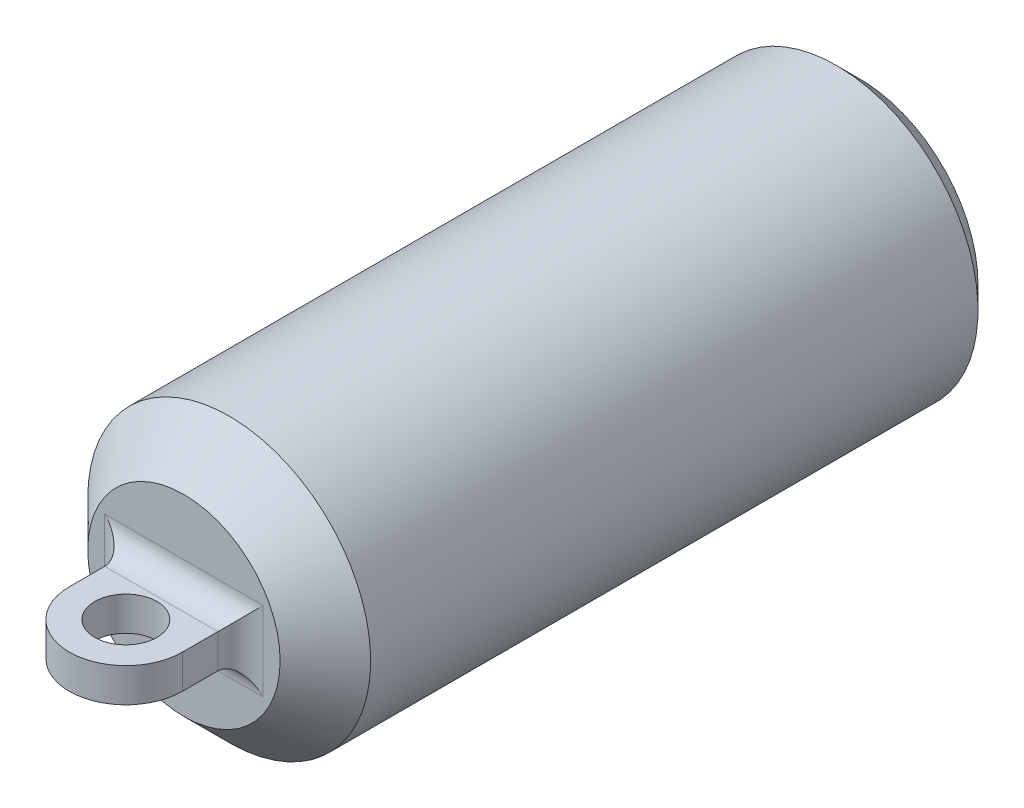
SolidWorks part; units mm, degrees
ref_plane "Front Plane" through (0, 0, 0) normal (0, 0, 1) x (1, 0, 0)
ref_plane "Top Plane" through (0, 0, 0) normal (0, 1, 0) x (1, 0, 0)
ref_plane "Right Plane" through (0, 0, 0) normal (1, 0, 0) x (0, 0, -1)
sketch "Sketch2" plane through (0, 0, 0) normal (0, 0, 1) x (1, 0, 0)
  circle A0 centre (0, 0) radius 15
  dimension "D1" = 30
sketch "Sketch3" plane through (0, 0, 0) normal (1, 0, 0) x (0, 0, -1)
  line L0 (-4.0824, 12.5) -> (4.0824, 12.5)
  line L4 (-10.591, 12.5) -> (-10.591, 0)
  line L5 (-13.9967, 0) -> (15.9606, 0) construction
  line L8 (0, 15) -> (0, -15) construction
  line L9 (16.5, 0) -> (-16.5, 0) construction
  line L10 (-10.591, 0) -> (4.0824, 0)
  line L13 (0, 16.5) -> (0, -16.5) construction
  line L16 (-4.0824, 12.5) -> (-10.591, 12.5)
  line L19 (4.0824, 12.5) -> (4.0824, 0)
  line L21 (-16.3935, 0) -> (16.347, 0) construction
  point P18 (0, -12.5)
  point P19 (0, 12.5)
  dimension "D1" = 12.5
revolve "Revolve2" add sketch "Sketch3" angle 360 about L21
sketch "Sketch4" plane through (0, 0, 0) normal (0, 1, 0) x (1, 0, 0)
  line L0 (-5, -15.7238) -> (-5, -10.591)
  line L1 (-12.5, -10.591) -> (12.5, -10.591) construction
  line L2 (-5, -10.591) -> (5, -10.591)
  line L3 (5, -10.591) -> (5, -15.7238)
  circle A0 centre (0, -15.7238) radius 2.75
  arc A1 (-5, -15.7238) -> (5, -15.7238) centre (0, -15.7238) ccw
  dimension "D1" = 5.5
  dimension "D2" = 10
extrude "Boss-Extrude1" add sketch "Sketch4" along normal mid plane 3
sketch "Sketch5" plane through (0, 0, -4.0824) normal (0, 0, -1) x (-1, 0, 0)
  circle A0 centre (0, 0) radius 12.5
  dimension "D1" = 25
extrude "Boss-Extrude2" add sketch "Sketch5" along normal blind 45
chamfer "Chamfer1" distance 4 angle 45 1 edges at (12.5, 0, 10.591)
fillet "Fillet1" radius 2 4 edges at (-5, 0, 10.591) (5, 0, 10.591) (0, -1.5, 10.591) (0, 1.5, 10.591)
chamfer "Chamfer2" distance 2 angle 45 1 edges at (-12.5, 0, -49.0824)
